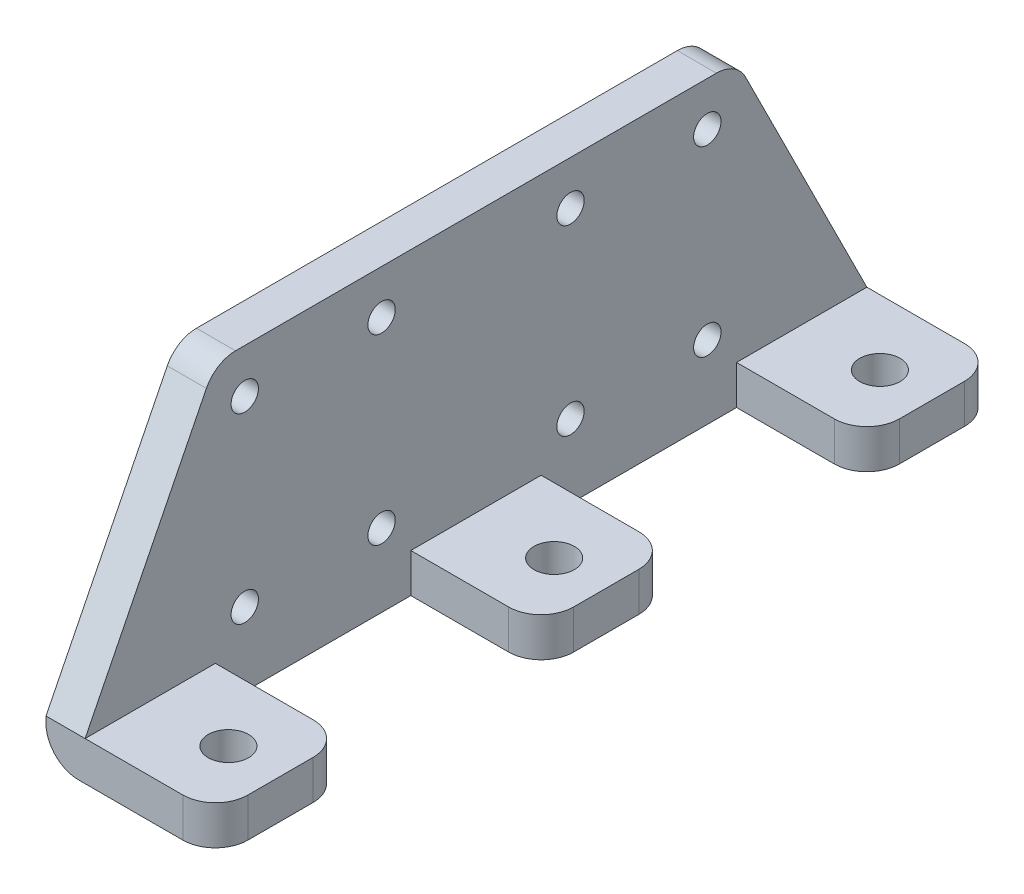
SolidWorks part; units mm, degrees
ref_plane "Alzado" through (0, 0, 0) normal (0, 0, 1) x (1, 0, 0)
ref_plane "Planta" through (0, 0, 0) normal (0, 1, 0) x (1, 0, 0)
ref_plane "Vista lateral" through (0, 0, 0) normal (1, 0, 0) x (0, 0, -1)
sketch "Croquis2" plane through (0, 58.7071, 0) normal (0, 1, 0) x (1, 0, 0)
  line L0 (-236.0976, -305) -> (-183.0976, -305) construction
  line L1 (-236.0976, -325) -> (-242.0976, -325)
  line L2 (-236.0976, -305) -> (-236.0976, -275)
  line L3 (-236.0976, -205) -> (-242.0976, -205)
  line L4 (-242.0976, -325) -> (-242.0976, -205)
  line L6 (-236.0976, -255) -> (-236.0976, -225) construction
  line L7 (-236.0976, -275) -> (-183.0976, -275) construction
  line L8 (-236.0976, -255) -> (-216.0976, -255)
  line L10 (-236.0976, -275) -> (-216.0976, -275)
  line L11 (-216.0976, -255) -> (-216.0976, -275)
  line L12 (-236.0976, -255) -> (-236.0976, -225)
  line L13 (-236.0976, -325) -> (-216.0976, -325)
  line L14 (-236.0976, -225) -> (-216.0976, -225)
  line L16 (-236.0976, -205) -> (-216.0976, -205)
  line L17 (-216.0976, -225) -> (-216.0976, -205)
  line L19 (-236.0976, -305) -> (-216.0976, -305)
  line L20 (-216.0976, -325) -> (-216.0976, -305)
  circle A0 centre (-224.0976, -215) radius 3.1
  circle A1 centre (-224.0976, -265) radius 3.1
  circle A2 centre (-224.0976, -315) radius 3.1
  point P4 (0, 0)
  point P23 (-216.0976, -215)
  point P26 (0, 0)
  point P27 (-216.0976, -265)
  point P30 (0, 0)
  point P33 (-224.0976, -314.8258)
  point P34 (0, 0)
  point P35 (-216.0976, -315)
  point P36 (0, 0)
  dimension "D6" = 6.2
  dimension "D1" = 6
  dimension "D2" = 20
  dimension "D3" = 20
  dimension "D4" = 20
  dimension "D5" = 8
extrude "Saliente-Extruir1" add sketch "Croquis2" along normal mid plane 6
sketch "Croquis4" plane through (-242.0976, 0, 0) normal (-1, 0, 0) x (0, 0, 1)
  line L0 (205, 61.7071) -> (325, 61.7071) construction
  line L1 (205, 61.7071) -> (325, 61.7071)
  line L2 (205, 61.7071) -> (225, 101.7071)
  line L3 (205, 61.7071) -> (325, 61.7071)
  line L5 (225, 101.7071) -> (305, 101.7071)
  line L7 (305, 101.7071) -> (325, 61.7071)
  circle A0 centre (250.49, 66.9521) radius 2.1 construction
  circle A1 centre (229.49, 66.9521) radius 2.1 construction
  circle A2 centre (279.49, 66.9521) radius 2.1 construction
  circle A3 centre (300.49, 66.9521) radius 2.1 construction
  circle A4 centre (279.49, 94.9521) radius 2.1 construction
  circle A5 centre (300.49, 94.9521) radius 2.1 construction
  circle A6 centre (229.49, 94.9521) radius 2.1 construction
  circle A7 centre (250.49, 94.9521) radius 2.1 construction
  circle A24 centre (250.49, 66.9521) radius 2.1
  circle A25 centre (229.49, 66.9521) radius 2.1
  circle A26 centre (279.49, 66.9521) radius 2.1
  circle A27 centre (300.49, 66.9521) radius 2.1
  circle A28 centre (279.49, 94.9521) radius 2.1
  circle A29 centre (300.49, 94.9521) radius 2.1
  circle A30 centre (229.49, 94.9521) radius 2.1
  circle A31 centre (250.49, 94.9521) radius 2.1
  point P5 (205.6462, 61.7071)
  point P6 (265, 101.7071)
  point P7 (265, 61.7071)
  point P8 (237.1782, 118.1243)
  point P9 (291.4193, 61.7071)
  point P10 (325.6015, 61.7071)
  line M8 (325, 61.7071) -> (205, 61.7071)
  dimension "D1" = 40
  dimension "D2" = 80
extrude "Saliente-Extruir2" add sketch "Croquis4" against normal blind 6 contours L7 L5 L2 M8
fillet "Redondeo1" radius 5 9 edges at (-242.0976, 55.7071, 265) (-216.0976, 58.7071, 305) (-216.0976, 58.7071, 325) (-216.0976, 58.7071, 275) (-216.0976, 58.7071, 255) (-216.0976, 58.7071, 225) (-216.0976, 58.7071, 205) (-239.0976, 101.7071, 225) (-239.0976, 101.7071, 305)
